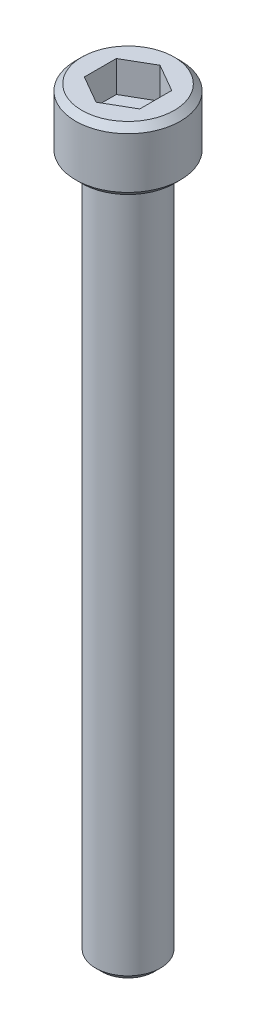
SolidWorks part; units mm, degrees
ref_plane "Front Plane" through (0, 0, 0) normal (0, 0, 1) x (1, 0, 0)
ref_plane "Top Plane" through (0, 0, 0) normal (0, 1, 0) x (1, 0, 0)
ref_plane "Right Plane" through (0, 0, 0) normal (1, 0, 0) x (0, 0, -1)
sketch "Sketch1" plane through (0, 0, 0) normal (0, 0, 1) x (1, 0, 0)
  line L0 (3.3655, 4.064) -> (0, 4.064)
  line L1 (0, 4.064) -> (0, 0)
  line L2 (0, 0) -> (3.3655, 0)
  line L3 (3.3655, 0) -> (3.3655, 4.064)
  line L4 (0, 4.064) -> (0, 0) construction
revolve "Revolve1" add sketch "Sketch1" angle 360 about L4
sketch "Sketch2" plane through (0, 0, 0) normal (0, -1, 0) x (1, 0, 0)
  circle A0 centre (0, 0) radius 2.0828
extrude "Boss-Extrude1" add sketch "Sketch2" along normal blind 44.45
sketch "Sketch3" plane through (0, 4.064, 0) normal (0, 1, 0) x (-1, 0, 0)
  line L0 (-1.778, -1.0265) -> (0, -2.0531)
  line L1 (0, -2.0531) -> (1.778, -1.0265)
  line L2 (1.778, -1.0265) -> (1.778, 1.0265)
  line L3 (1.778, 1.0265) -> (0, 2.0531)
  line L4 (0, 2.0531) -> (-1.778, 1.0265)
  line L5 (-1.778, 1.0265) -> (-1.778, -1.0265)
extrude "Cut-Extrude1" cut sketch "Sketch3" against normal blind 2
chamfer "Chamfer1" distance 0.4 angle 45 3 edges at (0, 4.064, -3.3655) (0, -44.45, -2.0828) (0, 0, -3.3655)
